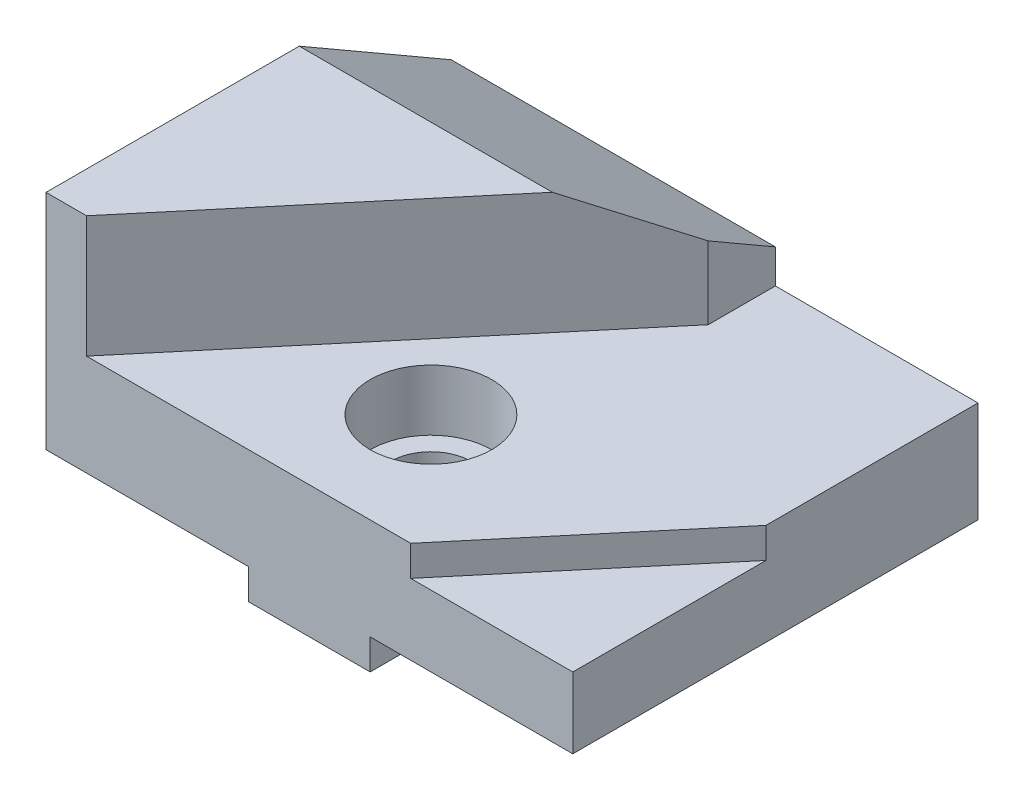
SolidWorks part; units mm, degrees
material "Nickel"
ref_plane "Plan de face" through (0, 0, 0) normal (0, 0, 1) x (1, 0, 0)
ref_plane "Plan de dessus" through (0, 0, 0) normal (0, 1, 0) x (1, 0, 0)
ref_plane "Plan de droite" through (0, 0, 0) normal (1, 0, 0) x (0, 0, -1)
sketch "Esquisse1" plane through (0, 0, 0) normal (0, 0, 1) x (1, 0, 0)
  line L0 (0, 0) -> (31.75, 0)
  line L1 (31.75, 0) -> (31.75, -4.7625)
  line L2 (31.75, -4.7625) -> (50.8, -4.7625)
  line L3 (50.8, -4.7625) -> (50.8, 0)
  line L4 (50.8, 0) -> (82.55, 0)
  line L5 (82.55, 0) -> (82.55, 34.925)
  line L6 (82.55, 34.925) -> (0, 34.925)
  line L7 (0, 34.925) -> (0, 0)
  dimension "D1" = 19.05
  dimension "D2" = 82.55
  dimension "D3" = 31.75
  dimension "D4" = 4.7625
  dimension "D5" = 39.6875
extrude "Boss.-Extru.1" add sketch "Esquisse1" along normal blind 63.5
chamfer "Chanfrein1" distance 23.8125 angle 30 1 edges at (41.275, 34.925, 0)
sketch "Esquisse2" plane through (0, 34.925, 0) normal (0, 1, 0) x (1, 0, 0)
  line L0 (50.8, 0) -> (50.8, -10.5266)
  line L1 (0, 0) -> (82.55, 0) construction
  line L2 (50.8, -10.5266) -> (6.35, -63.5)
  line L3 (82.55, -63.5) -> (0, -63.5) construction
  line L4 (6.35, -63.5) -> (82.55, -63.5)
  line L5 (82.55, -63.5) -> (82.55, 0)
  line L6 (82.55, 0) -> (50.8, 0)
  line L7 (0, -63.5) -> (0, -23.8125) construction
  dimension "D1" = 31.75
  dimension "D2" = 40
  dimension "D3" = 6.35
extrude "Enlèv. mat.-Extru.1" cut sketch "Esquisse2" against normal blind 19.05
hole_wizard "Chambrage pour vis à tête ronde bombée #01" positions "Esquisse4" profile "Esquisse3" counterbore size "#0" standard "Ansi Inch" end condition through all
sketch "Esquisse4" plane through (0, 15.875, 0) normal (0, 1, 0) x (1, 0, 0)
  line L0 (6.35, -63.5) -> (82.55, -63.5) construction
  line L1 (31.75, -63.5) -> (31.75, 0) construction
  point P0 (41.275, -44.45)
  dimension "D1" = 19.05
  dimension "D2" = 9.525
sketch "Esquisse3" plane through (41.275, 15.875, 44.45) normal (1, 0, 0) x (0, 0, 1)
  line L0 (0, 0) -> (0, 20.6375)
  line L1 (0, 20.6375) -> (6.35, 20.6375)
  line L3 (6.35, 20.6375) -> (6.35, 9.525)
  line L4 (6.35, 9.525) -> (9.525, 9.525)
  line L5 (9.525, 9.525) -> (9.525, 0)
  line L7 (9.525, 0) -> (0, 0)
  line L11 (0, -6.35) -> (0, 107.95) construction
  dimension "Diamètre du perçage jusqu'au prochain" = 12.7
  dimension "Profondeur du perçage jusqu'au prochain" = 20.6375
  dimension "Diamètre du chambrage" = 19.05
  dimension "Profondeur du chambrage" = 9.525
sketch "Esquisse5" plane through (0, 15.875, 0) normal (0, 1, 0) x (1, 0, 0)
  line L0 (57.15, -63.5) -> (82.55, -63.5)
  line L1 (6.35, -63.5) -> (82.55, -63.5) construction
  line L2 (82.55, -63.5) -> (82.55, -33.2295)
  line L3 (82.55, -63.5) -> (82.55, 0) construction
  line L4 (82.55, -33.2295) -> (57.15, -63.5)
  line L5 (50.8, -10.5266) -> (6.35, -63.5) construction
  dimension "D1" = 25.4
extrude "Enlèv. mat.-Extru.2" cut sketch "Esquisse5" against normal blind 4.7625
